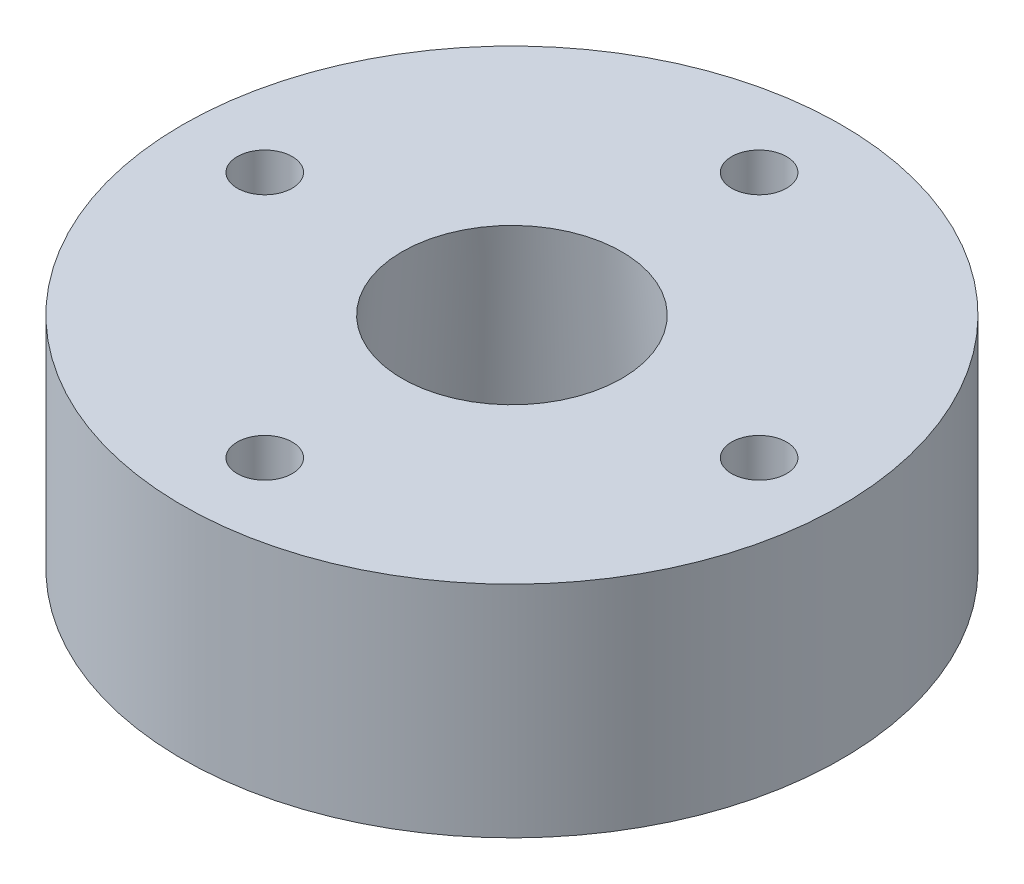
SolidWorks part; units mm, degrees
ref_plane "Front Plane" through (0, 0, 0) normal (0, 0, 1) x (1, 0, 0)
ref_plane "Top Plane" through (0, 0, 0) normal (0, 1, 0) x (1, 0, 0)
ref_plane "Right Plane" through (0, 0, 0) normal (1, 0, 0) x (0, 0, -1)
sketch "Sketch2" plane through (0, 0, 0) normal (0, 0, 1) x (1, 0, 0)
  line L0 (-19.05, 12.7) -> (-19.05, -12.7) construction
  line L1 (19.05, -12.7) -> (-2.2948, -12.7)
  line L2 (19.05, -12.7) -> (19.05, 12.7)
  line L3 (-6.35, 12.7) -> (19.05, 12.7)
  line L4 (-2.3204, -12.7) -> (-2.2948, -12.7)
  line L9 (-6.35, 12.7) -> (-4.3202, -10.7019)
  line L10 (-4.3202, -10.7019) -> (-2.3204, -12.7)
  point P0 (0, 0)
  dimension "D1" = 12.7
  dimension "D2" = 25.4
revolve "Revolve2" add sketch "Sketch2" angle 360 about L0
fillet "Fillet1" radius 2 2 edges at (-33.7798, -10.7019, 0) (-35.7796, -12.7, 0)
sketch "Sketch3" plane through (0, 12.7, 0) normal (0, 1, 0) x (1, 0, 0)
  line L0 (-19.05, 38.1) -> (-19.05, -38.1) construction
  line L1 (19.05, 0) -> (-57.15, 0) construction
  circle A0 centre (-19.05, 0) radius 38.1 construction
  circle A1 centre (-19.05, 28.575) radius 3.175
  circle A2 centre (9.525, 0) radius 3.175
  circle A3 centre (-19.05, -28.575) radius 3.175
  circle A4 centre (-47.625, 0) radius 3.175
  point P11 (-19.05, 0)
  point P19 (-19.05, 0)
  dimension "D1" = 4
  dimension "D2" = 28.575
  dimension "D3" = 6.35
extrude "Cut-Extrude1" cut sketch "Sketch3" against normal through all
